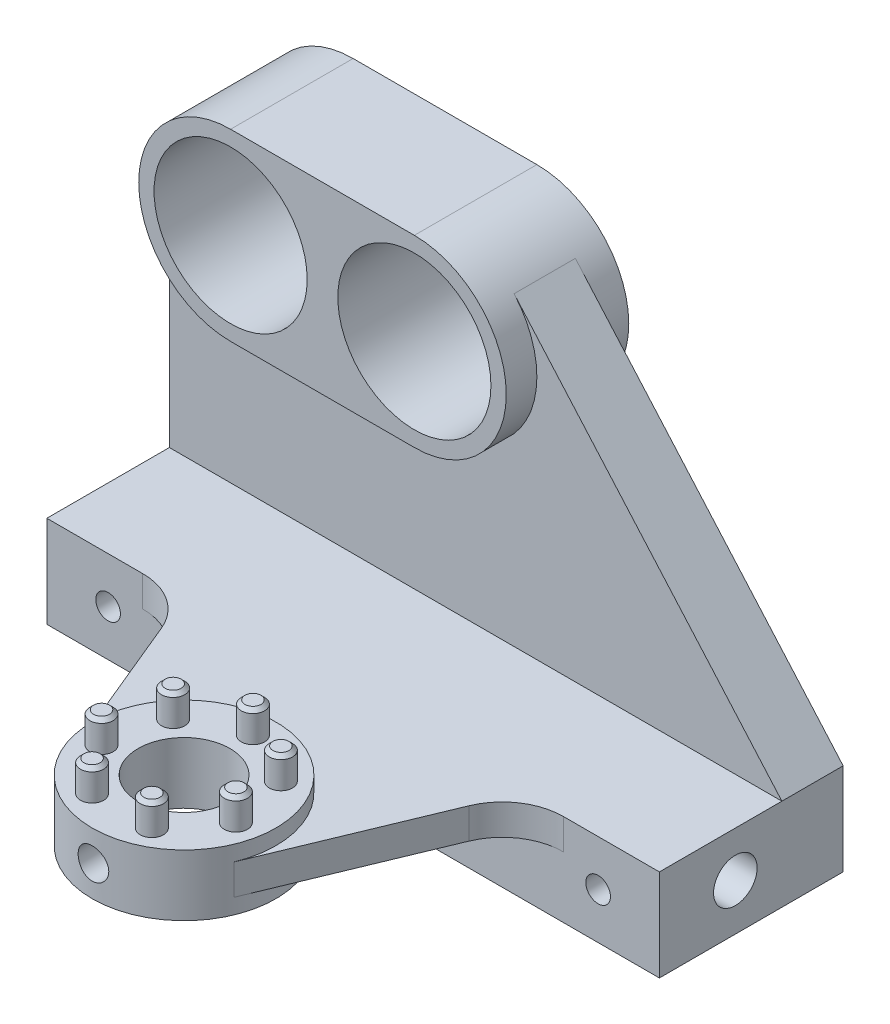
SolidWorks part; units mm, degrees
material "AISI 316 Stainless Steel Sheet (SS)"
ref_plane "Front" through (0, 0, 0) normal (0, 0, 1) x (1, 0, 0)
ref_plane "Top" through (0, 0, 0) normal (0, 1, 0) x (1, 0, 0)
ref_plane "Right" through (0, 0, 0) normal (1, 0, 0) x (0, 0, -1)
sketch "Sketch1" plane through (0, 0, 0) normal (0, 1, 0) x (1, 0, 0)
  line L1 (0, 0) -> (127, 0)
  line L2 (0, 0) -> (0, 38.1)
  line L3 (0, 38.1) -> (127, 38.1)
  line L4 (127, 0) -> (127, 38.1)
  dimension "D1" = 127
  dimension "D2" = 38.1
extrude "Boss-Extrude1" add sketch "Sketch1" against normal blind 19.05
ref_plane "Plane1" through (0, 0, 0) normal (0, 1, 0) x (1, 0, 0)
sketch "Sketch2" plane through (0, 0, 0) normal (0, 1, 0) x (1, 0, 0)
  line L0 (63.5, 38.1) -> (63.5, -35.052) construction
  line L1 (127, 38.1) -> (0, 38.1) construction
  line L2 (28.3614, 0) -> (98.6386, 0)
  line L3 (81.0999, -42.3421) -> (98.6386, 0)
  line L4 (45.9001, -42.3421) -> (28.3614, 0)
  line L5 (0, 0) -> (127, 0) construction
  arc A0 (45.9001, -42.3421) -> (81.0999, -42.3421) centre (63.5, -35.052) ccw
  dimension "D2" = 38.1
  dimension "D1" = 73.152
  dimension "D3" = 22.5
  dimension "D4" = 22.5
extrude "Boss-Extrude2" add sketch "Sketch2" against normal blind 6.35
fillet "Fillet1" radius 12.7 2 edges at (28.3614, -3.175, 0) (98.6386, -3.175, 0)
ref_plane "Plane2" through (0, -3.175, 0) normal (0, 1, 0) x (1, 0, 0)
sketch "Sketch3" plane through (0, -3.175, 0) normal (0, 1, 0) x (1, 0, 0)
  circle A0 centre (63.5, -35.052) radius 19.05
extrude "Boss-Extrude3" add sketch "Sketch3" along normal mid plane 12.7
ref_plane "Plane3" through (0, 0, -38.1) normal (0, 0, 1) x (1, 0, 0)
sketch "Sketch4" plane through (0, 0, -38.1) normal (0, 0, 1) x (1, 0, 0)
  line L0 (0, 0) -> (0, 50.8)
  line L1 (0, -19.05) -> (127, -19.05) construction
  line L2 (19.05, 50.8) -> (57.15, 50.8) construction
  line L3 (19.05, 69.85) -> (57.15, 69.85)
  line L5 (127, 0) -> (71.4768, 63.3556)
  line L6 (0, 0) -> (127, 0)
  arc A1 (71.4768, 63.3556) -> (57.15, 69.85) centre (57.15, 50.8) ccw
  arc A2 (19.05, 69.85) -> (0, 50.8) centre (19.05, 50.8) ccw
  point P7 (38.1, 50.8)
  dimension "D3" = 38.1
  dimension "D1" = 69.85
extrude "Boss-Extrude4" add sketch "Sketch4" along normal blind 12.7
ref_plane "Plane4" through (0, 0, -31.75) normal (0, 0, 1) x (1, 0, 0)
sketch "Sketch7" plane through (0, 0, -31.75) normal (0, 0, 1) x (1, 0, 0)
  line L0 (19.05, 50.8) -> (57.15, 50.8) construction
  line L1 (19.05, 69.85) -> (57.15, 69.85)
  line L2 (19.05, 31.75) -> (57.15, 31.75)
  arc A0 (19.05, 69.85) -> (19.05, 31.75) centre (19.05, 50.8) ccw
  arc A1 (57.15, 31.75) -> (57.15, 69.85) centre (57.15, 50.8) ccw
  point P2 (38.1, 50.8)
  point P7 (0, 0)
  point P8 (0, 0)
  point P12 (0, 50.8)
extrude "Boss-Extrude6" add sketch "Sketch7" along normal mid plane 25.4
hole_wizard "3/8 (1.25) Diameter Hole1" positions "3DSketch1" profile "Sketch8" hole size "3/8" standard "ANSI Inch" end condition through all
sketch3d "3DSketch1"
  line L0 (19.05, 50.8, -38.1) -> (19.05, 50.8, -44.45) construction
  line L1 (57.15, 50.8, -38.1) -> (57.15, 50.8, -44.45) construction
  point P0 (19.05, 50.8, -19.05)
  point P4 (57.15, 50.8, -19.05)
sketch "Sketch8" plane through (19.05, 50.8, -19.05) normal (1, 0, 0) x (0, -1, 0)
  line L0 (0, 0) -> (0, 25.4)
  line L1 (0, 25.4) -> (15.875, 25.4)
  line L2 (15.875, 25.4) -> (15.875, 0)
  line L5 (15.875, 0) -> (0, 0)
  line L11 (0, -6.35) -> (0, 107.95) construction
  dimension "Thru Hole Dia." = 31.75
  dimension "Thru Hole Depth" = 25.4
hole_wizard "1/4-20 Tapped Hole1" positions "3DSketch2" profile "Sketch9" tap size "1/4-20" standard "ANSI Inch" end condition through all
sketch3d "3DSketch2"
  line L0 (0, -19.05, 0) -> (127, -19.05, 0) construction
  line L1 (0, -19.05, 0) -> (0, 0, 0) construction
  point P0 (12.7, -9.525, 0)
  point P2 (114.3, -9.525, 0)
  dimension "D1" = 9.525
  dimension "D2" = 12.7
  dimension "D3" = 9.525
  dimension "D4" = 101.6
sketch "Sketch9" plane through (12.7, -9.525, 0) normal (1, 0, 0) x (0, -1, 0)
  line L0 (0, 0) -> (0, 44.45)
  line L1 (0, 44.45) -> (2.5527, 44.45)
  line L2 (2.5527, 44.45) -> (2.5527, 0)
  line L5 (2.5527, 0) -> (0, 0)
  line L11 (0, -6.35) -> (0, 107.95) construction
  dimension "Thru Tap Drill Dia." = 5.1054
  dimension "Thru Tap Drill Depth" = 44.45
cosmetic thread "Hole Thread1" parameters "D2"=6.35
cosmetic thread "Hole Thread2" parameters "D2"=6.35
ref_plane "Plane5" through (0, 0, 54.61) normal (0, 0, 1) x (1, 0, 0)
sketch "Sketch11" plane through (0, 0, 54.61) normal (0, 0, 1) x (1, 0, 0)
  line L0 (82.55, 3.175) -> (44.45, 3.175) construction
  line L2 (0, -19.05) -> (0, 0) construction
  circle A0 centre (63.5, -3.175) radius 3.175
  dimension "D1" = 6.35
  dimension "D2" = 63.5
extrude "Cut-Extrude1" cut sketch "Sketch11" against normal blind 19.05
hole_wizard "1/4 (0.356) Diameter Hole1" positions "3DSketch4" profile "Sketch12" hole size "1/4" standard "ANSI Inch" end condition through all
sketch3d "3DSketch4"
  line L0 (127, -19.05, -38.1) -> (127, 0, -38.1) construction
  line L1 (127, -19.05, 0) -> (127, -19.05, -38.1) construction
  point P0 (127, -9.398, -15.748)
  dimension "D1" = 22.352
  dimension "D2" = 9.652
sketch "Sketch12" plane through (127, -9.398, -15.748) normal (0, 1, 0) x (0, 0, -1)
  line L0 (0, 0) -> (0, 127)
  line L1 (0, 127) -> (4.5212, 127)
  line L2 (4.5212, 127) -> (4.5212, 0)
  line L5 (4.5212, 0) -> (0, 0)
  line L11 (0, -6.35) -> (0, 107.95) construction
  dimension "Thru Hole Dia." = 9.0424
  dimension "Thru Hole Depth" = 127
hole_wizard "1/4 (0.75) Diameter Hole1" positions "3DSketch5" profile "Sketch13" hole size "1/4" standard "ANSI Inch" end condition through all
sketch3d "3DSketch5"
  line L0 (63.5, -9.525, 35.052) -> (63.5, 3.175, 35.052) construction
  point P0 (63.5, 3.175, 35.052)
sketch "Sketch13" plane through (63.5, 3.175, 35.052) normal (1, 0, 0) x (0, 0, 1)
  line L0 (0, 0) -> (0, 22.225)
  line L1 (0, 22.225) -> (9.525, 22.225)
  line L2 (9.525, 22.225) -> (9.525, 0)
  line L5 (9.525, 0) -> (0, 0)
  line L11 (0, -6.35) -> (0, 107.95) construction
  dimension "Thru Hole Dia." = 19.05
  dimension "Thru Hole Depth" = 22.225
ref_plane "Plane6" through (0, 3.175, 0) normal (0, 1, 0) x (1, 0, 0)
sketch "Sketch16" plane through (0, 3.175, 0) normal (0, 1, 0) x (1, 0, 0)
  circle A0 centre (63.5, -35.052) radius 14.2875 construction
  circle A1 centre (63.5, -20.7645) radius 2.413
  circle A2 centre (74.6704, -26.1439) radius 2.413
  circle A3 centre (77.4293, -38.2313) radius 2.413
  circle A4 centre (69.6991, -47.9246) radius 2.413
  circle A5 centre (57.3009, -47.9246) radius 2.413
  circle A6 centre (49.5707, -38.2313) radius 2.413
  circle A7 centre (52.3296, -26.1439) radius 2.413
  dimension "D1" = 7
extrude "Boss-Extrude7" add sketch "Sketch16" along normal blind 6.35
chamfer "Chamfer1" distance 0.762 angle 45 7 edges at (77.4293, 9.525, 40.6443) (57.3009, 9.525, 50.3376) (69.6991, 9.525, 50.3376) (74.6704, 9.525, 28.5569) (63.5, 9.525, 23.1775) (52.3296, 9.525, 28.5569) (49.5707, 9.525, 40.6443)
